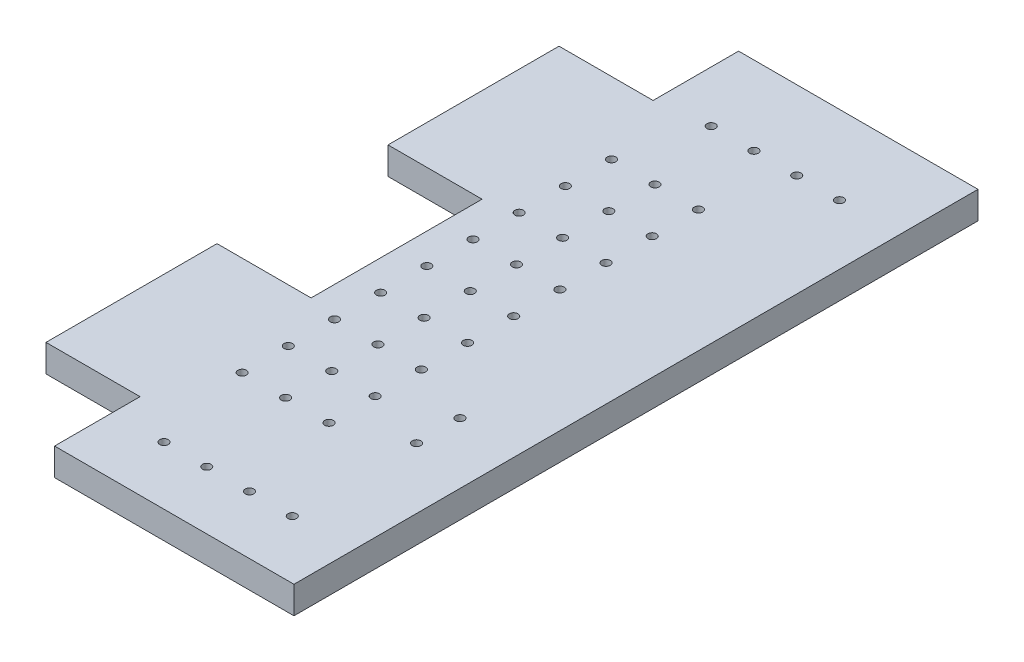
SolidWorks part; units mm, degrees
ref_plane "정면" through (0, 0, 0) normal (0, 0, 1) x (1, 0, 0)
ref_plane "윗면" through (0, 0, 0) normal (0, 1, 0) x (1, 0, 0)
ref_plane "우측면" through (0, 0, 0) normal (1, 0, 0) x (0, 0, -1)
sketch "스케치1" plane through (0, 0, 0) normal (0, 1, 0) x (1, 0, 0)
  line L1 (0, 0) -> (19.5, 0)
  line L2 (0, 0) -> (0, 40)
  line L3 (0, 40) -> (19.5, 40)
  line L4 (19.5, 0) -> (19.5, 40)
  dimension "D1" = 19.5
  dimension "D2" = 40
extrude "보스-돌출1" add sketch "스케치1" along normal blind 1.6
sketch "스케치2" plane through (0, 1.6, 0) normal (0, 1, 0) x (1, 0, 0)
  line L0 (0, 40) -> (0, 0) construction
  line L1 (0, 0) -> (5.5, 0)
  line L2 (0, 0) -> (0, 5)
  line L3 (0, 5) -> (5.5, 5)
  line L4 (5.5, 0) -> (5.5, 5)
  line L5 (0, 40) -> (5.5, 40)
  line L6 (0, 40) -> (0, 35)
  line L7 (0, 35) -> (5.5, 35)
  line L8 (5.5, 40) -> (5.5, 35)
  line L9 (0, 25) -> (5.5, 25)
  line L10 (0, 25) -> (0, 15)
  line L11 (0, 15) -> (5.5, 15)
  line L12 (5.5, 25) -> (5.5, 15)
  dimension "D1" = 5
  dimension "D2" = 5.5
  dimension "D3" = 10
  dimension "D4" = 10
extrude "컷-돌출1" cut sketch "스케치2" against normal through all
sketch "스케치3" plane through (0, 1.6, 0) normal (0, 1, 0) x (1, 0, 0)
  line L0 (19.5, 40) -> (5.5, 40) construction
  line L5 (5.5, 35) -> (5.5, 40) construction
  line L6 (5.5, 0) -> (5.5, 5) construction
  line L7 (5.5, 0) -> (19.5, 0) construction
  line L8 (5.5, 15) -> (5.5, 25) construction
  point P0 (8.5, 35.4)
  point P11 (15.9416, 10.7257)
  point P23 (7.27, 30.8)
  point P33 (8.5, 3.4)
  dimension "D1" = 4.6
  dimension "D2" = 3
  dimension "D3" = 3
  dimension "D4" = 3.4
  dimension "D5" = 4.6
  dimension "D6" = 1.77
hole_wizard "Ø0.5 (0.5) 지름 구멍1" positions "스케치6" profile "스케치7" hole size "Ø0.5" standard "ISO" end condition through all
sketch "스케치6" plane through (0, 1.6, 0) normal (0, 1, 0) x (1, 0, 0)
  point P0 (8.5, 35.4)
sketch "스케치7" plane through (8.5, 1.6, -35.4) normal (1, 0, 0) x (0, 0, 1)
  line L0 (0, 0) -> (0, 1.6)
  line L1 (0, 1.6) -> (0.25, 1.6)
  line L2 (0.25, 1.6) -> (0.25, 0)
  line L5 (0.25, 0) -> (0, 0)
  line L11 (0, -6.35) -> (0, 107.95) construction
  dimension "관통 구멍 지름" = 0.5
  dimension "관통 구멍 깊이" = 1.6
pattern_linear "선형 패턴1" count 4 spacing 2.5 along (1, 0, 0) of "Ø0.5 (0.5) 지름 구멍1"
hole_wizard "Ø0.5 (0.5) 지름 구멍2" positions "스케치8" profile "스케치9" hole size "Ø0.5" standard "ISO" end condition through all
sketch "스케치8" plane through (0, 1.6, 0) normal (0, 1, 0) x (1, 0, 0)
  point P0 (7.27, 30.8)
sketch "스케치9" plane through (7.27, 1.6, -30.8) normal (1, 0, 0) x (0, 0, 1)
  line L0 (0, 0) -> (0, 1.6)
  line L1 (0, 1.6) -> (0.25, 1.6)
  line L2 (0.25, 1.6) -> (0.25, 0)
  line L5 (0.25, 0) -> (0, 0)
  line L11 (0, -6.35) -> (0, 107.95) construction
  dimension "관통 구멍 지름" = 0.5
  dimension "관통 구멍 깊이" = 1.6
pattern_linear "선형 패턴2" count 3 spacing 2.54 along (1, 0, 0) count 9 spacing 2.7 along (0, 0, 1) of "Ø0.5 (0.5) 지름 구멍2"
hole_wizard "Ø0.5 (0.5) 지름 구멍3" positions "스케치10" profile "스케치11" hole size "Ø0.5" standard "ISO" end condition through all
sketch "스케치10" plane through (0, 1.6, 0) normal (0, 1, 0) x (1, 0, 0)
  point P0 (15.9416, 10.7257)
sketch "스케치11" plane through (15.9416, 1.6, -10.7257) normal (1, 0, 0) x (0, 0, 1)
  line L0 (0, 0) -> (0, 1.6)
  line L1 (0, 1.6) -> (0.25, 1.6)
  line L2 (0.25, 1.6) -> (0.25, 0)
  line L5 (0.25, 0) -> (0, 0)
  line L11 (0, -6.35) -> (0, 107.95) construction
  dimension "관통 구멍 지름" = 0.5
  dimension "관통 구멍 깊이" = 1.6
pattern_linear "선형 패턴3" count 2 spacing 2.54 along (0, 0, -1) of "Ø0.5 (0.5) 지름 구멍3"
hole_wizard "Ø0.5 (0.5) 지름 구멍4" positions "스케치12" profile "스케치13" hole size "Ø0.5" standard "ISO" end condition through all
sketch "스케치12" plane through (0, 1.6, 0) normal (0, 1, 0) x (1, 0, 0)
  point P0 (8.5, 3.4)
sketch "스케치13" plane through (8.5, 1.6, -3.4) normal (1, 0, 0) x (0, 0, 1)
  line L0 (0, 0) -> (0, 1.6)
  line L1 (0, 1.6) -> (0.25, 1.6)
  line L2 (0.25, 1.6) -> (0.25, 0)
  line L5 (0.25, 0) -> (0, 0)
  line L11 (0, -6.35) -> (0, 107.95) construction
  dimension "관통 구멍 지름" = 0.5
  dimension "관통 구멍 깊이" = 1.6
pattern_linear "선형 패턴4" count 4 spacing 2.5 along (1, 0, 0) of "Ø0.5 (0.5) 지름 구멍4"
equation "\"D4@스케치2\"=\"D3@스케치2\""
